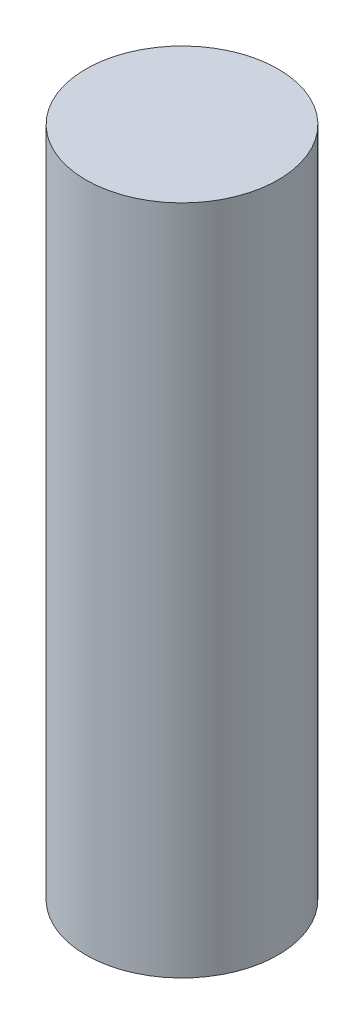
SolidWorks part; units mm, degrees
ref_plane "Plan de face" through (0, 0, 0) normal (0, 0, 1) x (1, 0, 0)
ref_plane "Plan de dessus" through (0, 0, 0) normal (0, 1, 0) x (1, 0, 0)
ref_plane "Plan de droite" through (0, 0, 0) normal (1, 0, 0) x (0, 0, -1)
sketch "Esquisse1" plane through (0, 0, 0) normal (0, 1, 0) x (1, 0, 0)
  circle A0 centre (0, 0) radius 3.15
  dimension "D1" = 6.3
extrude "Boss.-Extru.1" add sketch "Esquisse1" along normal blind 22
